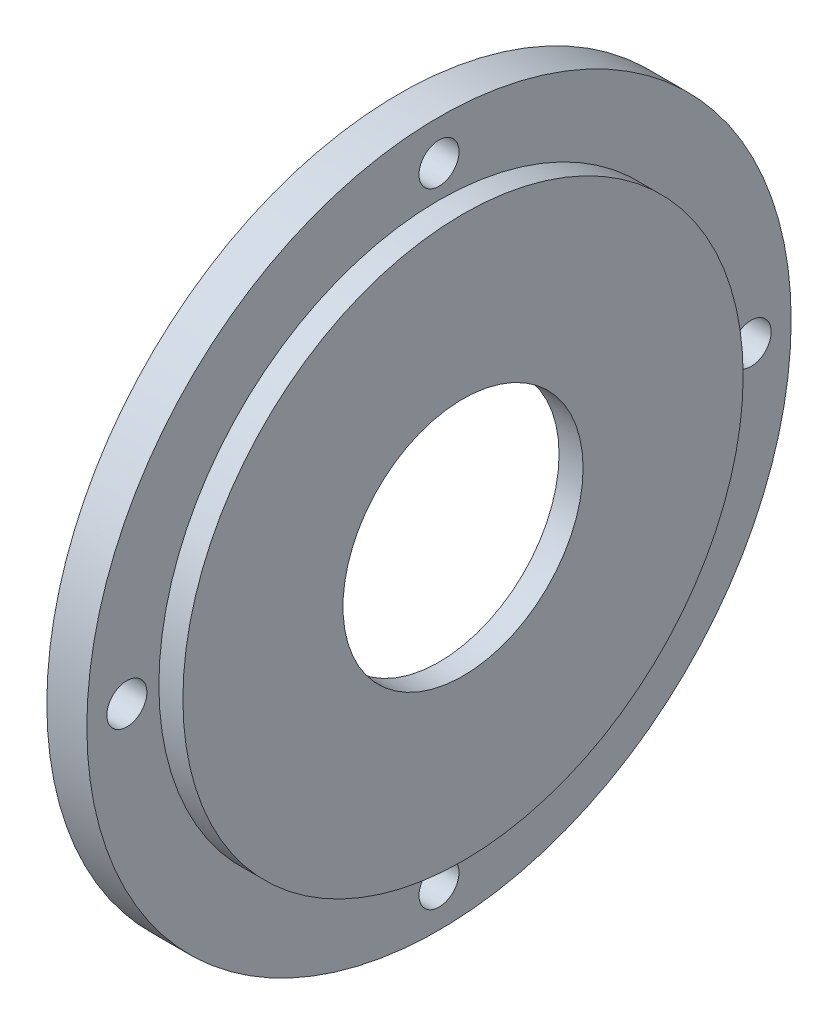
SolidWorks part; units mm, degrees
ref_plane "前视基准面" through (0, 0, 0) normal (0, 0, 1) x (1, 0, 0)
ref_plane "上视基准面" through (0, 0, 0) normal (0, 1, 0) x (1, 0, 0)
ref_plane "右视基准面" through (0, 0, 0) normal (1, 0, 0) x (0, 0, -1)
sketch "草图1" plane through (0, 0, 0) normal (1, 0, 0) x (0, 0, -1)
  circle A0 centre (0, 0) radius 27
  circle A1 centre (0, 0) radius 44
extrude "凸台-拉伸1" add sketch "草图1" along normal blind 5
sketch "草图2" plane through (5, 0, 0) normal (1, 0, 0) x (0, 0, -1)
  circle A0 centre (0, 0) radius 35
extrude "凸台-拉伸2" add sketch "草图2" along normal blind 3
sketch "草图3" plane through (5, 0, 0) normal (1, 0, 0) x (0, 0, -1)
  circle A0 centre (0, 39) radius 2.5
  circle A1 centre (39, 0) radius 2.5
  circle A2 centre (0, -39) radius 2.5
  circle A3 centre (-39, 0) radius 2.5
  point P11 (0, 0)
  dimension "D1" = 4
extrude "切除-拉伸1" cut sketch "草图3" against normal up to surface (5 mm away) up to face at (0, 0, -44)
sketch "草图4" plane through (8, 0, 0) normal (1, 0, 0) x (0, 0, -1)
  circle A0 centre (0, 0) radius 15
extrude "切除-拉伸2" cut sketch "草图4" against normal up to surface (8 mm away) up to face at (0, 39, -2.5)
